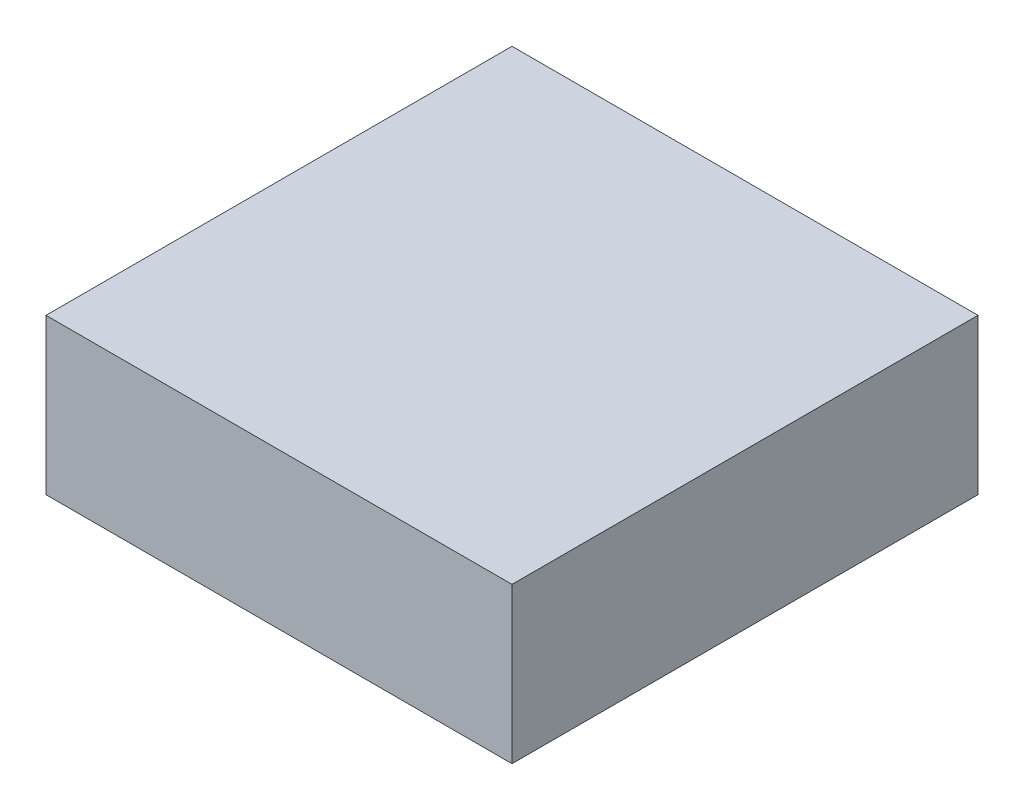
SolidWorks part; units mm, degrees
ref_plane "Front" through (0, 0, 0) normal (0, 0, 1) x (1, 0, 0)
ref_plane "Top" through (0, 0, 0) normal (0, 1, 0) x (1, 0, 0)
ref_plane "Right" through (0, 0, 0) normal (1, 0, 0) x (0, 0, -1)
sketch "Sketch11" plane through (0, 0, 0) normal (0, 1, 0) x (1, 0, 0)
  line L1 (-40.5, -40.5) -> (40.5, -40.5)
  line L2 (-40.5, -40.5) -> (-40.5, 40.5)
  line L3 (-40.5, 40.5) -> (40.5, 40.5)
  line L4 (40.5, -40.5) -> (40.5, 40.5)
  line L5 (-40.5, -40.5) -> (40.5, 40.5) construction
  line L6 (-40.5, 40.5) -> (40.5, -40.5) construction
  point P0 (0, 0)
  dimension "D1" = 81
extrude "Boss-Extrude1" add sketch "Sketch11" along normal blind 27
sketch "Sketch1" plane through (0, 0, 0) normal (0, 0, 1) x (1, 0, 0)
  line L0 (0, 25) -> (0, 10)
  line L1 (31.5, 19.8898) -> (31.5, -17.8473) construction
  line L2 (0, 0) -> (31.5, 0) construction
  line L3 (0, 25) -> (0, 0) construction
  line L4 (31.5, 0) -> (30.5, 0) construction
  line L5 (0, 10) -> (0, -10)
  line L6 (0, -10) -> (31.5, -10)
  line L7 (31.5, -10) -> (31.5, 0)
  spline S0 degree 3 poles (0, 25) (1.3715, 25) (4.0902, 24.3027) (10.7515, 17.1368) (25.5788, 15.0702) (31.0385, 6.4502) (31.5, 0) knots 0 0 0 0 0.091246 0.195023 0.675457 1 1 1 1
  spline S1 degree 3 poles (30.5, 0) (24.4624, 10.5881) (11.1572, 9.4928) (0, 10) knots 0 0 0 0 1 1 1 1 construction
  dimension "D1" = 25
  dimension "D4" = 31.5
  dimension "D5" = 20
  dimension "D2" = 1
  dimension "D3" = 15
revolve "Cut-Revolve1" cut sketch "Sketch1" angle 360 about L5
equation "\"CutAngle\"= 2"
